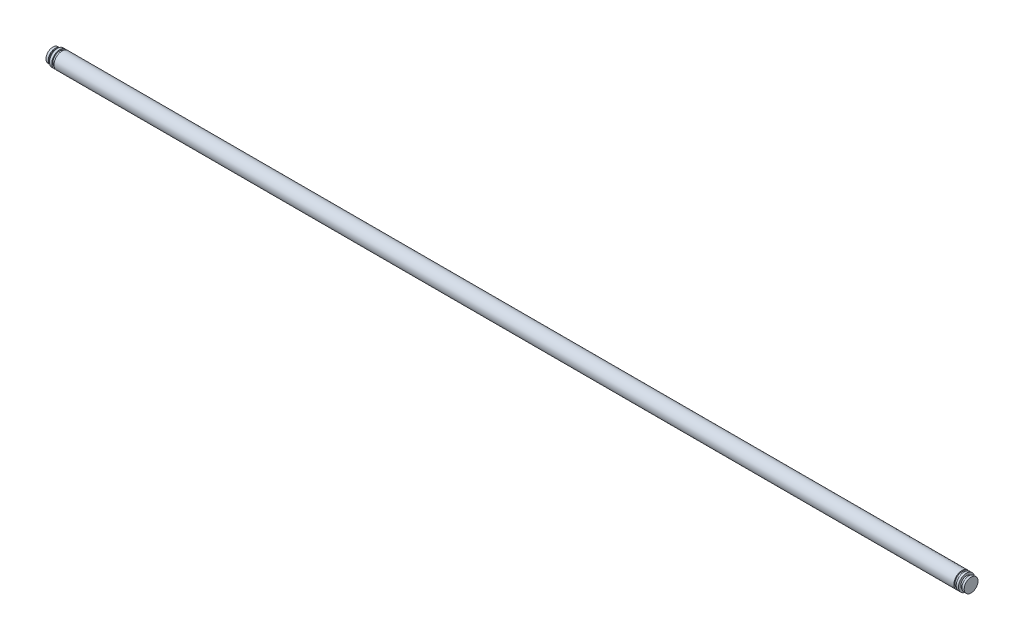
SolidWorks part; units mm, degrees
ref_plane "Front Plane" through (0, 0, 0) normal (0, 0, 1) x (1, 0, 0)
ref_plane "Top Plane" through (0, 0, 0) normal (0, 1, 0) x (1, 0, 0)
ref_plane "Right Plane" through (0, 0, 0) normal (1, 0, 0) x (0, 0, -1)
sketch "Sketch1" plane through (0, 0, 0) normal (1, 0, 0) x (0, 0, -1)
  circle A0 centre (0, 0) radius 3.5
  dimension "D1" = 7
extrude "Boss-Extrude1" add sketch "Sketch1" along normal mid plane 392 contours A0
sketch "Sketch6" plane through (196, 0, 0) normal (1, 0, 0) x (0, 0, -1)
  circle A0 centre (0, 0) radius 2.9994
extrude "Boss-Extrude4" add sketch "Sketch6" along normal blind 1
sketch "Sketch7" plane through (197, 0, 0) normal (1, 0, 0) x (0, 0, -1)
  circle A0 centre (0, 0) radius 3.5
extrude "Boss-Extrude5" add sketch "Sketch7" along normal blind 1
sketch "Sketch8" plane through (198, 0, 0) normal (1, 0, 0) x (0, 0, -1)
  circle A0 centre (0, 0) radius 2.5027
extrude "Boss-Extrude6" add sketch "Sketch8" along normal blind 1
sketch "Sketch9" plane through (199, 0, 0) normal (1, 0, 0) x (0, 0, -1)
  circle A0 centre (0, 0) radius 3.0042
extrude "Boss-Extrude7" add sketch "Sketch9" along normal blind 1
sketch "Sketch10" plane through (-196, 0, 0) normal (-1, 0, 0) x (0, 0, 1)
  circle A0 centre (0, 0) radius 3
extrude "Boss-Extrude8" add sketch "Sketch10" along normal blind 1
sketch "Sketch11" plane through (-197, 0, 0) normal (-1, 0, 0) x (0, 0, 1)
  circle A0 centre (0, 0) radius 3.5
extrude "Boss-Extrude9" add sketch "Sketch11" along normal blind 1
sketch "Sketch12" plane through (-198, 0, 0) normal (-1, 0, 0) x (0, 0, 1)
  circle A0 centre (0, 0) radius 2.5048
extrude "Boss-Extrude10" add sketch "Sketch12" along normal blind 1
sketch "Sketch13" plane through (-199, 0, 0) normal (-1, 0, 0) x (0, 0, 1)
  circle A0 centre (0, 0) radius 3.0027
extrude "Boss-Extrude11" add sketch "Sketch13" along normal blind 1
